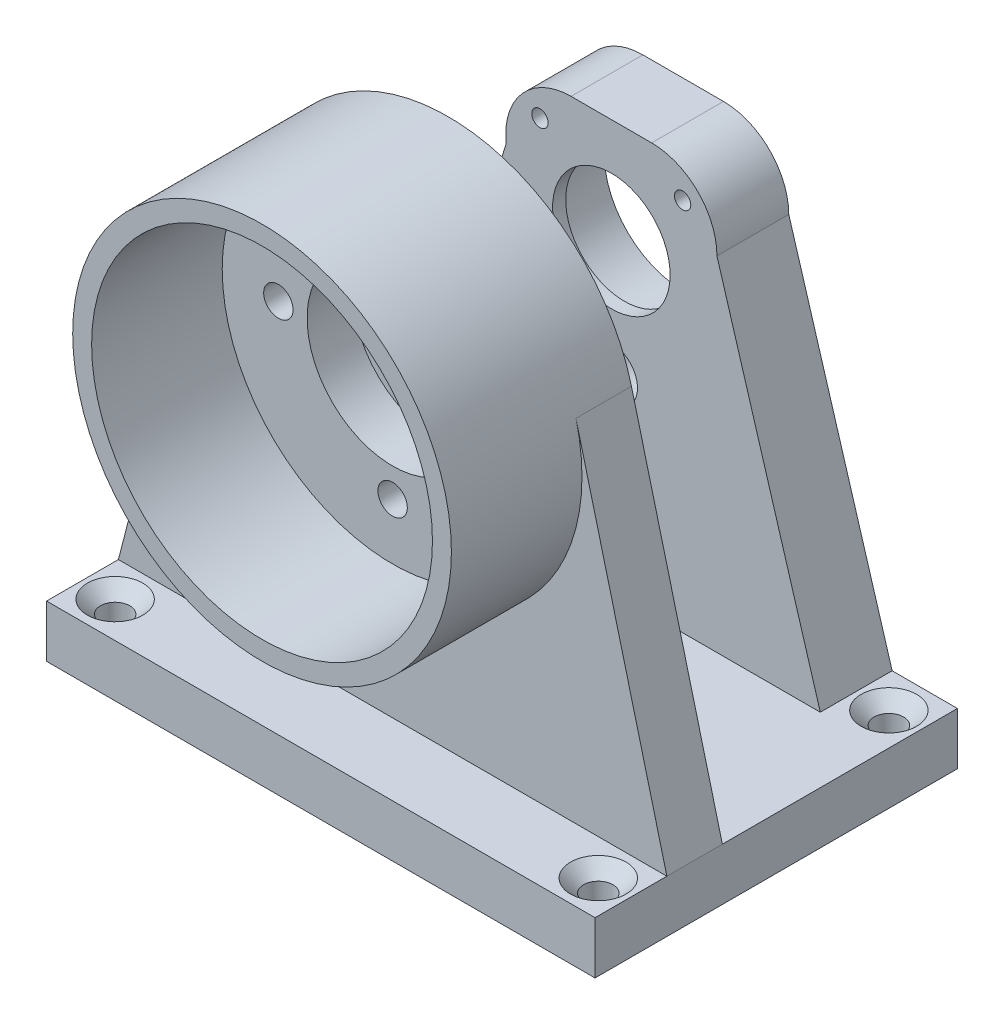
SolidWorks part; units mm, degrees
material "PET"
ref_plane "Piano frontale" through (0, 0, 0) normal (0, 0, 1) x (1, 0, 0)
ref_plane "Piano superiore" through (0, 0, 0) normal (0, 1, 0) x (1, 0, 0)
ref_plane "Piano destro" through (0, 0, 0) normal (1, 0, 0) x (0, 0, -1)
sketch "Schizzo1" plane through (0, 0, 0) normal (0, 0, 1) x (1, 0, 0)
  line L0 (-16.1, 0) -> (0, 0) construction
  line L1 (-6.1713, 16.1) -> (6.1713, 16.1)
  line L3 (-17, -54.5) -> (17, -54.5)
  line L5 (0, 0) -> (16.1, 0) construction
  line L7 (-17, -54.5) -> (-42, -54.5)
  line L11 (17, -54.5) -> (42, -54.5)
  line L16 (42, -54.5) -> (42, -46.5)
  line L18 (-42, -54.5) -> (-42, -46.5)
  line L20 (42, -46.5) -> (32, -46.5)
  line L21 (32, -46.5) -> (16.1713, 6.1)
  line L22 (-42, -46.5) -> (-32, -46.5)
  line L23 (-32, -46.5) -> (-16.1, 4.9079)
  circle A0 centre (0, 0) radius 12.1
  arc A1 (16.1713, 6.1) -> (6.1713, 16.1) centre (6.1713, 6.1) ccw
  arc A2 (-16.1, 4.9079) -> (-6.1713, 16.1) centre (-6.1713, 6.1) cw
  point P13 (0, -54.5)
  point P14 (0, 16.1)
  dimension "D1" = 24.2
  dimension "D3" = 25
  dimension "D4" = 10
  dimension "D7" = 8
  dimension "D2" = 16.1
  dimension "D5" = 54.5
  dimension "D6" = 34
  dimension "D8" = 10
  dimension "D9" = 10
extrude "Estrusione-Estrusione1" add sketch "Schizzo1" along normal blind 11
sketch "Schizzo2" plane through (0, 0, 11) normal (0, 0, 1) x (1, 0, 0)
  circle A0 centre (0, 0) radius 9
  circle A1 centre (0, 0) radius 12.1
  dimension "D1" = 18
extrude "Estrusione-Estrusione2" add sketch "Schizzo2" against normal blind 2
sketch "Schizzo3" plane through (0, -46.5, 0) normal (0, 1, 0) x (1, 0, 0)
  line L0 (32, -11) -> (42, 0) construction
  line L1 (-42, -11) -> (-32, 0) construction
  circle A0 centre (37, -5.5) radius 2.25
  circle A1 centre (-37, -5.5) radius 2.25
  dimension "D1" = 4.5
extrude "Taglio-Estrusione1" cut sketch "Schizzo3" against normal through all
chamfer "Smusso1" distance 2 angle 45 2 edges at (-37, -46.5, 7.75) (37, -46.5, 7.75)
sketch "Schizzo4" plane through (0, 0, 0) normal (0, 0, -1) x (-1, 0, 0)
  line L0 (-8.5791, 8.5329) -> (-13.2424, 13.1711) construction
  line L1 (8.6056, 8.5061) -> (13.2834, 13.1299) construction
  line L2 (0, -12.1) -> (0, -18.6772) construction
  arc A0 (-6.1713, 16.1) -> (-16.1713, 6.1) centre (-6.1713, 6.1) ccw construction
  arc A1 (16.1, 4.9079) -> (6.1713, 16.1) centre (6.1713, 6.1) ccw construction
  circle A2 centre (0, 0) radius 12.1 construction
  circle A3 centre (0, 0) radius 12.1 construction
  circle A4 centre (-10.9107, 10.852) radius 1.25
  circle A5 centre (10.9445, 10.818) radius 1.25
  circle A6 centre (0, -15.3886) radius 1.25
  dimension "D1" = 2.5
extrude "Taglio-Estrusione2" cut sketch "Schizzo4" against normal through all
sketch "Schizzo5" plane through (0, 0, 11) normal (0, 0, 1) x (1, 0, 0)
  line L0 (-42, -54.5) -> (42, -54.5) construction
  line L1 (-42, -46.5) -> (42, -46.5)
  line L2 (-42, -46.5) -> (-42, -54.5)
  line L3 (-42, -54.5) -> (42, -54.5)
  line L4 (42, -46.5) -> (42, -54.5)
  line L5 (42, -54.5) -> (42, -46.5) construction
extrude "Estrusione-Estrusione3" add sketch "Schizzo5" along normal blind 25
sketch "Schizzo6" plane through (0, 0, 36) normal (0, 0, 1) x (1, 0, 0)
  line L0 (-42, -46.5) -> (-28.0737, 7.2709)
  line L1 (42, -46.5) -> (28.0737, 7.2709)
  line L3 (-42, -46.5) -> (42, -46.5)
  line L4 (-42, -46.5) -> (-42, -54.5)
  line L5 (-42, -54.5) -> (42, -54.5)
  line L6 (42, -46.5) -> (42, -54.5)
  circle A0 centre (0, 0) radius 29
  circle A1 centre (0, 0) radius 6
  circle A2 centre (0, 0) radius 17.5
  circle A3 centre (0, 17.5) radius 2.25
  circle A4 centre (17.5, 0) radius 2.25
  circle A5 centre (0, -17.5) radius 2.25
  circle A6 centre (-17.5, 0) radius 2.25
  line M5 (-42, -46.5) -> (-42, -54.5)
  line M6 (-42, -54.5) -> (42, -54.5)
  line M7 (42, -54.5) -> (42, -46.5)
  line M8 (42, -46.5) -> (-42, -46.5)
  dimension "D1" = 58
  dimension "D2" = 12
  dimension "D3" = 35
  dimension "D4" = 4.5
extrude "Estrusione-Estrusione4" add sketch "Schizzo6" along normal blind 1.5 contours A0 L0 L1 M8 | A0 A6 A2 A3 A4 A5 | A6 A2 A5 A4 A3 A1 | M8 M5 M6 M7
sketch "Schizzo7" plane through (0, 0, 37.5) normal (0, 0, 1) x (1, 0, 0)
  line L5 (42, -46.5) -> (28.0737, 7.2709)
  line L6 (-28.0737, 7.2709) -> (-42, -46.5)
  line L7 (-42, -46.5) -> (-42, -54.5)
  line L8 (-42, -54.5) -> (42, -54.5)
  line L9 (42, -54.5) -> (42, -46.5)
  line L10 (42, -46.5) -> (28.0737, 7.2709)
  line L11 (-28.0737, 7.2709) -> (-42, -46.5)
  line L12 (-42, -46.5) -> (-42, -54.5)
  line L13 (-42, -54.5) -> (42, -54.5)
  line L14 (42, -54.5) -> (42, -46.5)
  circle A0 centre (0, -17.5) radius 2.25 construction
  arc A1 (28.0737, 7.2709) -> (-28.0737, 7.2709) centre (0, 0) ccw
  arc A2 (28.0737, 7.2709) -> (-28.0737, 7.2709) centre (0, 0) ccw
  circle A3 centre (17.5, 0) radius 2.25 construction
  circle A4 centre (0, 17.5) radius 2.25 construction
  circle A5 centre (-17.5, 0) radius 2.25 construction
  circle A6 centre (0, -17.5) radius 2.25
  circle A7 centre (17.5, 0) radius 2.25
  circle A8 centre (0, 17.5) radius 2.25
  circle A9 centre (-17.5, 0) radius 2.25
  circle A10 centre (0, 0) radius 13.1
  dimension "D2" = 26.2
  dimension "D1" = 0
extrude "Estrusione-Estrusione5" add sketch "Schizzo7" along normal blind 7
sketch "Schizzo8" plane through (0, 0, 44.5) normal (0, 0, 1) x (1, 0, 0)
  circle A0 centre (0, 0) radius 26.1
  circle A1 centre (0, 0) radius 29
  dimension "D1" = 52.2
extrude "Estrusione-Estrusione6" add sketch "Schizzo8" along normal blind 20
sketch "Schizzo9" plane through (0, 0, 0) normal (0, 0, -1) x (-1, 0, 0)
  circle A0 centre (0, -17.5) radius 2.25 construction
  circle A1 centre (0, -17.5) radius 2.25
  circle A2 centre (0, -17.5) radius 4
  circle M5 centre (0, -15.3886) radius 1.25
  dimension "D1" = 8
extrude "Taglio-Estrusione4" cut sketch "Schizzo9" against normal up to next contours A2 A1 M5 | A1 M5 | A1 M5 | A1 M5
sketch "Schizzo10" plane through (0, 0, 44.5) normal (0, 0, 1) x (1, 0, 0)
  line L0 (42, -54.5) -> (42, -46.5) construction
  line L1 (-42, -46.5) -> (42, -46.5)
  line L2 (-42, -46.5) -> (-42, -54.5)
  line L3 (-42, -54.5) -> (42, -54.5)
  line L4 (-32, -46.5) -> (32, -46.5)
  line L5 (32, -46.5) -> (16.1713, 6.1)
  line L6 (6.1713, 16.1) -> (-6.1713, 16.1)
  line L7 (-16.1, 4.9079) -> (-32, -46.5)
  line L8 (-32, -46.5) -> (32, -46.5)
  line L9 (32, -46.5) -> (16.1713, 6.1)
  line L10 (6.1713, 16.1) -> (-6.1713, 16.1)
  line L11 (-16.1, 4.9079) -> (-32, -46.5)
  line L12 (42, -46.5) -> (42, -54.5)
  line L13 (-42, -54.5) -> (42, -54.5) construction
  arc A2 (16.1713, 6.1) -> (6.1713, 16.1) centre (6.1713, 6.1) ccw
  arc A3 (-6.1713, 16.1) -> (-16.1, 4.9079) centre (-6.1713, 6.1) ccw
  arc A4 (16.1713, 6.1) -> (6.1713, 16.1) centre (6.1713, 6.1) ccw
  arc A5 (-6.1713, 16.1) -> (-16.1, 4.9079) centre (-6.1713, 6.1) ccw
  line M9 (-42, -46.5) -> (-42, -54.5)
  line M10 (-42, -54.5) -> (42, -54.5)
  line M11 (42, -54.5) -> (42, -46.5)
  dimension "D1" = 0
extrude "Estrusione-Estrusione7" add sketch "Schizzo10" along normal blind 11 contours L1 M9 M10 M11
sketch "Schizzo11" plane through (0, -46.5, 0) normal (0, 1, 0) x (1, 0, 0)
  line L0 (-42, -50) -> (-37, -50)
  line L1 (-42, -55.5) -> (-42, -44.5) construction
  line L2 (42, -50) -> (37, -50)
  line L3 (42, -55.5) -> (42, -44.5) construction
  circle A0 centre (-37, -50) radius 2.25
  circle A1 centre (37, -50) radius 2.25
  circle A2 centre (37, -5.5) radius 2.25 construction
  dimension "D1" = 5
extrude "Taglio-Estrusione5" cut sketch "Schizzo11" against normal through all
chamfer "Smusso2" distance 2 angle 45 2 edges at (-37, -46.5, 52.25) (37, -46.5, 52.25)
